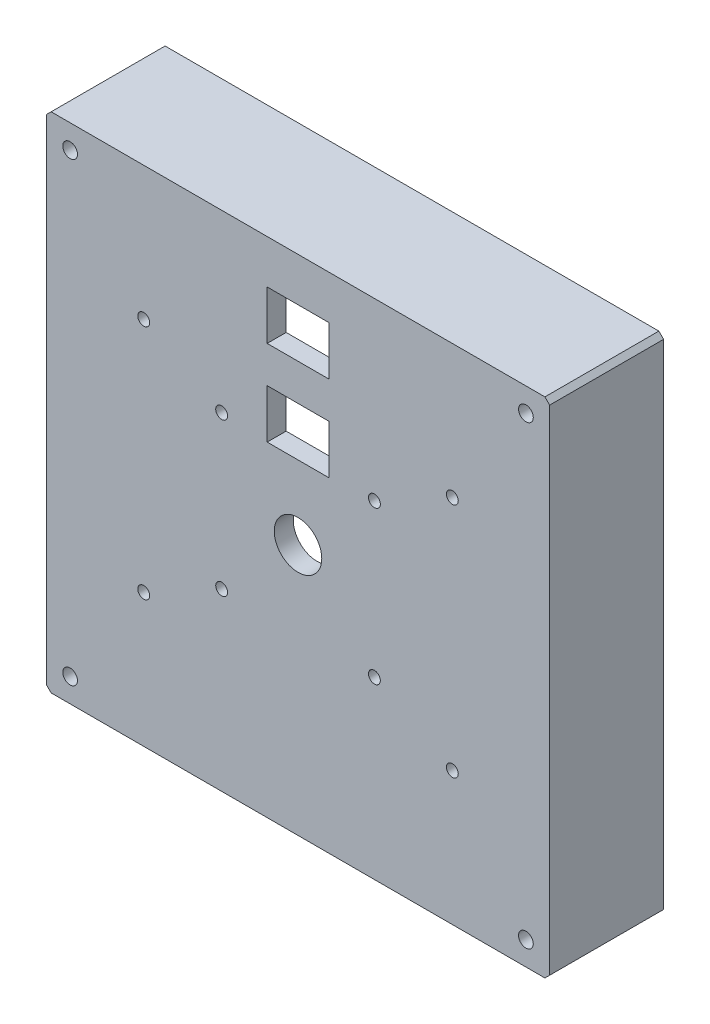
SolidWorks part; units mm, degrees
ref_plane "Front Plane" through (0, 0, 0) normal (0, 0, 1) x (1, 0, 0)
ref_plane "Top Plane" through (0, 0, 0) normal (0, 1, 0) x (1, 0, 0)
ref_plane "Right Plane" through (0, 0, 0) normal (1, 0, 0) x (0, 0, -1)
sketch "Sketch1" plane through (0, 0, 0) normal (0, 0, 1) x (1, 0, 0)
  line L0 (0, 43) -> (0, -43) construction
  line L1 (-53, 53) -> (53, 53)
  line L2 (-53, 53) -> (-53, -53)
  line L3 (-53, -53) -> (53, -53)
  line L4 (53, 53) -> (53, -53)
  line L5 (-43, 0) -> (43, 0) construction
  point P5 (-53, 0)
  point P7 (0, 53)
  dimension "D1" = 106
  dimension "D2" = 106
extrude "Boss-Extrude1" add sketch "Sketch1" against normal blind 4
sketch "Sketch2" plane through (0, 0, -4) normal (0, 0, -1) x (-1, 0, 0)
  line L0 (53, 53) -> (53, -53) construction
  line L1 (-53, 53) -> (53, 53)
  line L2 (-53, 53) -> (-53, -53)
  line L3 (-53, -53) -> (53, -53)
  line L4 (53, 53) -> (53, -53)
  line L5 (-48, 41) -> (-48, -41)
  line L10 (-48, -41) -> (-41, -48)
  line L11 (-41, -48) -> (41, -48)
  line L12 (41, -48) -> (48, -41)
  line L13 (48, -41) -> (48, 41)
  line L14 (48, 41) -> (41, 48)
  line L15 (41, 48) -> (-41, 48)
  line L16 (-41, 48) -> (-48, 41)
  dimension "D1" = 5
  dimension "D2" = 5
  dimension "D3" = 5
  dimension "D4" = 5
  dimension "D5" = 12
  dimension "D6" = 12
  dimension "D7" = 12
  dimension "D8" = 12
  dimension "D9" = 12
extrude "Boss-Extrude2" add sketch "Sketch2" along normal blind 20
sketch "Sketch6" plane through (0, 0, 0) normal (0, 0, 1) x (1, 0, 0)
  line L1 (-53, 53) -> (53, 53)
  line L2 (-53, 53) -> (-53, -53)
  line L3 (-53, -53) -> (53, -53)
  line L4 (53, 53) -> (53, -53)
  circle A0 centre (0, 0) radius 48
  dimension "D1" = 96
sketch "Sketch7" plane through (0, 0, 0) normal (0, 0, 1) x (1, 0, 0)
  line L1 (-53, 53) -> (53, 53) construction
  line L2 (-53, 53) -> (-53, -53) construction
  line L3 (-53, -53) -> (53, -53) construction
  line L4 (53, 53) -> (53, -53) construction
  circle A0 centre (-48, 48) radius 1.55
  circle A1 centre (48, 48) radius 1.55
  circle A2 centre (-48, -48) radius 1.55
  circle A3 centre (48, -48) radius 1.55
  dimension "D1" = 5
  dimension "D3" = 3.1
  dimension "D6" = 3.1
  dimension "D9" = 3.1
  dimension "D12" = 3.1
  dimension "D2" = 5
  dimension "D4" = 5
  dimension "D5" = 5
  dimension "D7" = 5
  dimension "D8" = 5
  dimension "D10" = 5
  dimension "D11" = 5
extrude "Cut-Extrude2" cut sketch "Sketch7" against normal blind 50
sketch "Sketch8" plane through (0, 0, 0) normal (0, 0, 1) x (1, 0, 0)
  line L0 (-16.0867, -16.0867) -> (16.0867, 16.0867) construction
  line L1 (-6.5, 43.8) -> (6.5, 43.8)
  line L2 (-6.5, 43.8) -> (-6.5, 33.5)
  line L3 (-6.5, 33.5) -> (6.5, 33.5)
  line L4 (6.5, 43.8) -> (6.5, 33.5)
  line L5 (-6.5, 25.8) -> (6.5, 25.8)
  line L6 (-6.5, 25.8) -> (-6.5, 15.5)
  line L7 (-6.5, 15.5) -> (6.5, 15.5)
  line L8 (6.5, 25.8) -> (6.5, 15.5)
  line L9 (-16.0867, 16.0867) -> (16.0867, -16.0867) construction
  line L10 (0, 53) -> (0, -53) construction
  line L11 (-53, 53) -> (53, 53) construction
  line L12 (-53, 53) -> (-53, -53) construction
  line L13 (-53, -53) -> (53, -53) construction
  line L14 (53, 53) -> (53, -53) construction
  line L15 (13.2, 0) -> (-13.2, 0) construction
  line L16 (-4.5, 23.8) -> (4.5, 23.8) construction
  line L17 (-4.5, 23.8) -> (-4.5, 21.5) construction
  line L18 (-4.5, 21.5) -> (4.5, 21.5) construction
  line L19 (4.5, 23.8) -> (4.5, 21.5) construction
  line L20 (-4.5, 41.8) -> (4.5, 41.8) construction
  line L21 (-4.5, 41.8) -> (-4.5, 39.5) construction
  line L22 (-4.5, 39.5) -> (4.5, 39.5) construction
  line L23 (4.5, 41.8) -> (4.5, 39.5) construction
  line L24 (-32.5, 24.9) -> (32.5, 24.9) construction
  line L25 (-32.5, 24.9) -> (-32.5, -24.9) construction
  line L26 (-32.5, -24.9) -> (32.5, -24.9) construction
  line L27 (32.5, 24.9) -> (32.5, -24.9) construction
  line L28 (-53, 0) -> (53, 0) construction
  circle A0 centre (32.5, 24.9) radius 1.25
  circle A1 centre (-32.5, 24.9) radius 1.25
  circle A2 centre (-32.5, -24.9) radius 1.25
  circle A3 centre (32.5, -24.9) radius 1.25
  circle A4 centre (16.0867, -16.0867) radius 1.25
  circle A5 centre (-16.0867, -16.0867) radius 1.25
  circle A6 centre (16.0867, 16.0867) radius 1.25
  circle A7 centre (-16.0867, 16.0867) radius 1.25
  circle A8 centre (0, 0) radius 5
  point P22 (32.5, 0)
  point P25 (-32.5, 0)
  dimension "D6" = 2.5
  dimension "D7" = 2.5
  dimension "D8" = 2.5
  dimension "D9" = 2.5
  dimension "D10" = 2.5
  dimension "D11" = 2.5
  dimension "D12" = 2.5
  dimension "D13" = 2.5
  dimension "D22" = 10
  dimension "D1" = 65
  dimension "D2" = 49.8
  dimension "D3" = 45.5
  dimension "D4" = 45.5
  dimension "D5" = 45
  dimension "D14" = 2
  dimension "D15" = 6
  dimension "D16" = 2
  dimension "D17" = 2
  dimension "D18" = 2
  dimension "D19" = 6
  dimension "D20" = 2
  dimension "D21" = 2
extrude "Cut-Extrude3" cut sketch "Sketch8" against normal blind 10
sketch "Sketch9" plane through (0, 0, -4) normal (0, 0, 1) x (1, 0, 0)
  line L0 (0, 46) -> (0, -46) construction
  line L1 (-53, 53) -> (53, 53) construction
  line L2 (-53, 53) -> (-53, -53) construction
  line L3 (-53, -53) -> (53, -53) construction
  line L4 (53, 53) -> (53, -53) construction
  line L5 (-39.5, 46) -> (39.5, 46) construction
  line L6 (-39.5, 46) -> (-39.5, -46) construction
  line L7 (-39.5, -46) -> (39.5, -46) construction
  line L8 (39.5, 46) -> (39.5, -46) construction
  line L9 (-39.5, 0) -> (39.5, 0) construction
  line L18 (37.4, 39.7988) -> (35.7012, 38.1)
  line L19 (-35.7012, 38.1) -> (-33.2988, 38.1)
  line L20 (-33.2988, 38.1) -> (-31.6, 39.7988)
  line L21 (-31.6, 39.7988) -> (-31.6, 42.2012)
  line L22 (-31.6, 42.2012) -> (-33.2988, 43.9)
  line L23 (-33.2988, 43.9) -> (-35.7012, 43.9)
  line L24 (-35.7012, 43.9) -> (-37.4, 42.2012)
  line L25 (-37.4, 42.2012) -> (-37.4, 39.7988)
  line L26 (-37.4, 39.7988) -> (-35.7012, 38.1)
  line L27 (37.4, 42.2012) -> (37.4, 39.7988)
  line L28 (35.7012, 43.9) -> (37.4, 42.2012)
  line L29 (33.2988, 43.9) -> (35.7012, 43.9)
  line L30 (31.6, 42.2012) -> (33.2988, 43.9)
  line L31 (31.6, 39.7988) -> (31.6, 42.2012)
  line L32 (33.2988, 38.1) -> (31.6, 39.7988)
  line L33 (35.7012, 38.1) -> (33.2988, 38.1)
  line L34 (35.7012, -38.1) -> (33.2988, -38.1)
  line L35 (33.2988, -38.1) -> (31.6, -39.7988)
  line L36 (31.6, -39.7988) -> (31.6, -42.2012)
  line L37 (31.6, -42.2012) -> (33.2988, -43.9)
  line L38 (33.2988, -43.9) -> (35.7012, -43.9)
  line L39 (35.7012, -43.9) -> (37.4, -42.2012)
  line L40 (37.4, -42.2012) -> (37.4, -39.7988)
  line L41 (37.4, -39.7988) -> (35.7012, -38.1)
  line L42 (-37.4, -39.7988) -> (-35.7012, -38.1)
  line L43 (-37.4, -42.2012) -> (-37.4, -39.7988)
  line L44 (-35.7012, -43.9) -> (-37.4, -42.2012)
  line L45 (-33.2988, -43.9) -> (-35.7012, -43.9)
  line L46 (-31.6, -42.2012) -> (-33.2988, -43.9)
  line L47 (-31.6, -39.7988) -> (-31.6, -42.2012)
  line L48 (-33.2988, -38.1) -> (-31.6, -39.7988)
  line L49 (-35.7012, -38.1) -> (-33.2988, -38.1)
  circle A0 centre (-34.5, 41) radius 4.5
  circle A4 centre (-34.5, 41) radius 2.9 construction
  circle A5 centre (34.5, 41) radius 4.5
  circle A6 centre (34.5, -41) radius 4.5
  circle A7 centre (-34.5, -41) radius 2.9 construction
  circle A8 centre (-34.5, -41) radius 4.5
  dimension "D1" = 9
  dimension "D2" = 13.5
  dimension "D3" = 13.5
  dimension "D4" = 7
  dimension "D5" = 7
  dimension "D6" = 5
  dimension "D7" = 5
  dimension "D8" = 5.8
extrude "Boss-Extrude3" add sketch "Sketch9" against normal blind 4
sketch "Sketch14" plane through (0, -53, 0) normal (0, -1, 0) x (1, 0, 0)
  line L0 (0, 0) -> (0, -24) construction
  line L5 (-53, 0) -> (53, 0) construction
  line L6 (-53, 0) -> (-53, -24) construction
  line L7 (-53, -24) -> (53, -24) construction
  line L8 (53, 0) -> (53, -24) construction
  line L10 (-6.5, -10.83) -> (6.5, -10.83) construction
  line L13 (-6.5, -6.83) -> (6.5, -6.83)
  line L14 (-6.5, -6.83) -> (-6.5, -14.83)
  line L15 (-6.5, -14.83) -> (6.5, -14.83)
  line L16 (6.5, -6.83) -> (6.5, -14.83)
  circle A0 centre (20, -10.83) radius 2.5
  point P10 (-6.5, -10.83)
  point P13 (6.5, -10.83)
  point P14 (0, -14.83)
  point P19 (-15.2378, -10.83)
  point P20 (22.3803, -10.83)
  dimension "D4" = 5
  dimension "D1" = 10.83
  dimension "D2" = 13
  dimension "D3" = 8
  dimension "D5" = 20
  dimension "D6" = 10.83
extrude "Cut-Extrude4" cut sketch "Sketch14" against normal blind 10
chamfer "Chamfer1" distance 1 4 edges at (53, 53, -12) (-53, 53, -12) (-53, -53, -12) (53, -53, -12)
chamfer "Chamfer2" distance 1 4 edges at (0, -53, -6.83) (6.5, -53, -10.83) (0, -53, -14.83) (-6.5, -53, -10.83)
sketch "Sketch15" plane through (48, 0, 0) normal (-1, 0, 0) x (0, 0, 1)
  line L0 (-12, -53) -> (-12, 53) construction
  line L1 (0, -53) -> (-24, -53) construction
  line L2 (0, -53) -> (0, 53) construction
  line L3 (0, 53) -> (-24, 53) construction
  line L4 (-24, -53) -> (-24, 53) construction
  circle A0 centre (-12, -23) radius 1.6
  circle A1 centre (-12, 23) radius 1.6
  dimension "D1" = 3.2
  dimension "D2" = 3.2
  dimension "D3" = 30
  dimension "D4" = 30
extrude "Cut-Extrude5" cut sketch "Sketch15" against normal blind 1 and the other way blind 97
chamfer "Chamfer3" distance 1 angle 45 2 edges at (20, -48, -8.33) (22.5, -53, -10.83)
